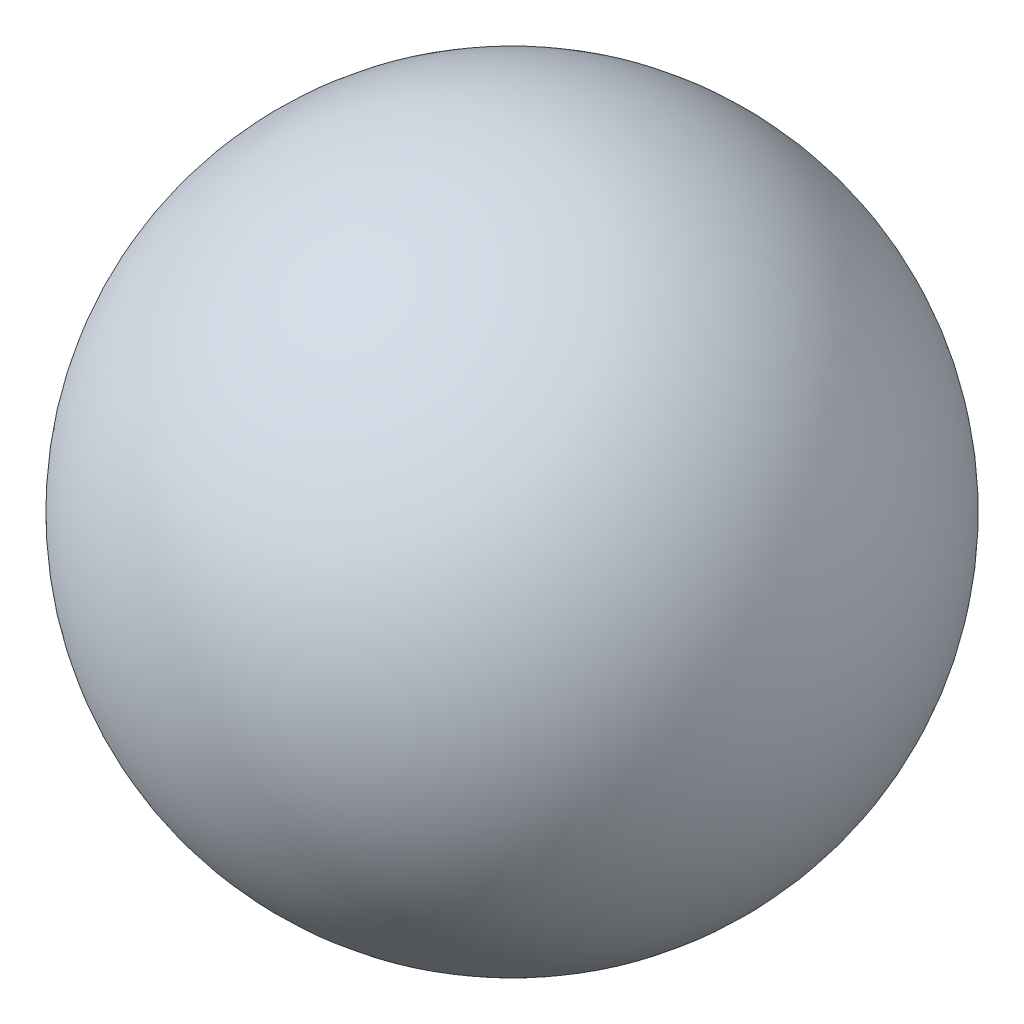
SolidWorks part; units mm, degrees
ref_plane "Plan de face" through (0, 0, 0) normal (0, 0, 1) x (1, 0, 0)
ref_plane "Plan de dessus" through (0, 0, 0) normal (0, 1, 0) x (1, 0, 0)
ref_plane "Plan de droite" through (0, 0, 0) normal (1, 0, 0) x (0, 0, -1)
sketch "Esquisse1" plane through (0, 0, 0) normal (0, 0, 1) x (1, 0, 0)
  line L0 (0, -8) -> (0, 0) construction
  line L1 (0, 0) -> (0, 8) construction
  line L2 (0, 8) -> (0, -8)
  arc A0 (0, 8) -> (0, -8) centre (0, 0) cw
  dimension "D1" = 8
revolve "Révolution1" add sketch "Esquisse1" angle 360 about L2
